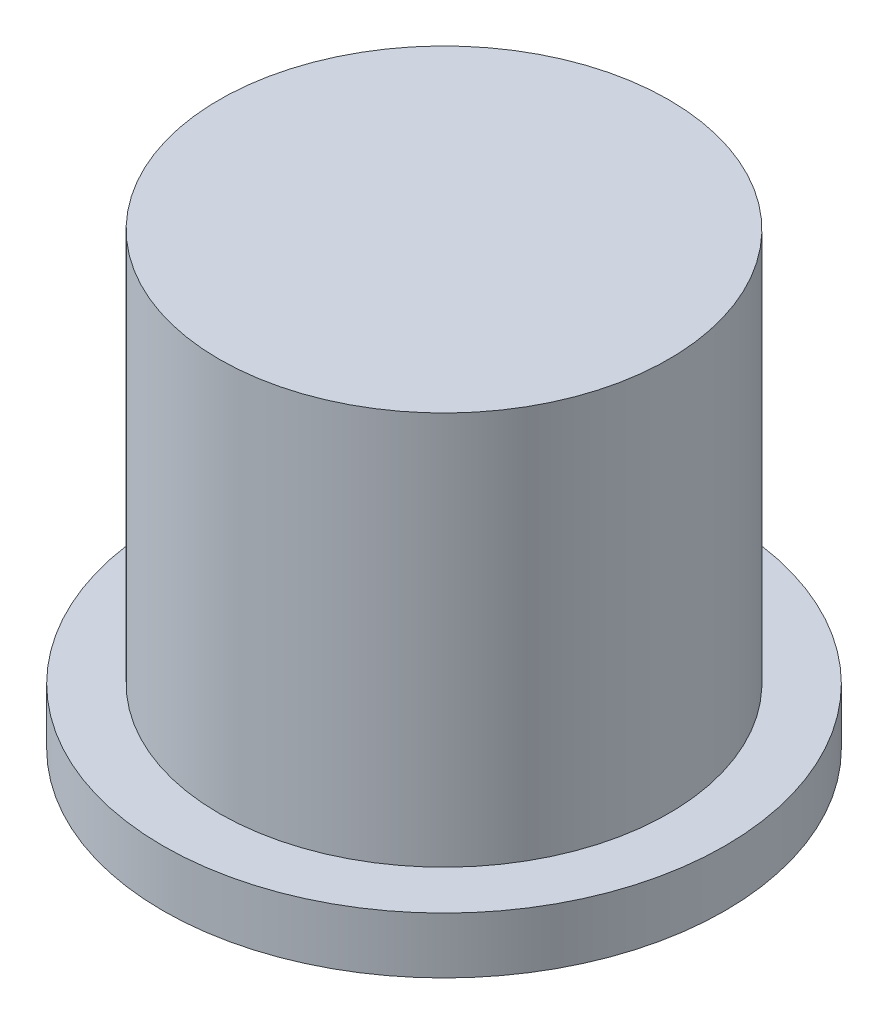
SolidWorks part; units mm, degrees
ref_plane "Front Plane" through (0, 0, 0) normal (0, 0, 1) x (1, 0, 0)
ref_plane "Top Plane" through (0, 0, 0) normal (0, 1, 0) x (1, 0, 0)
ref_plane "Right Plane" through (0, 0, 0) normal (1, 0, 0) x (0, 0, -1)
sketch "Sketch1" plane through (0, 0, 0) normal (0, 1, 0) x (1, 0, 0)
  circle A0 centre (0, 0) radius 10
  dimension "D1" = 20
extrude "Boss-Extrude1" add sketch "Sketch1" along normal blind 2
sketch "Sketch2" plane through (0, 2, 0) normal (0, 1, 0) x (1, 0, 0)
  circle A0 centre (0, 0) radius 8
  dimension "D1" = 16
extrude "Boss-Extrude2" add sketch "Sketch2" along normal blind 14
